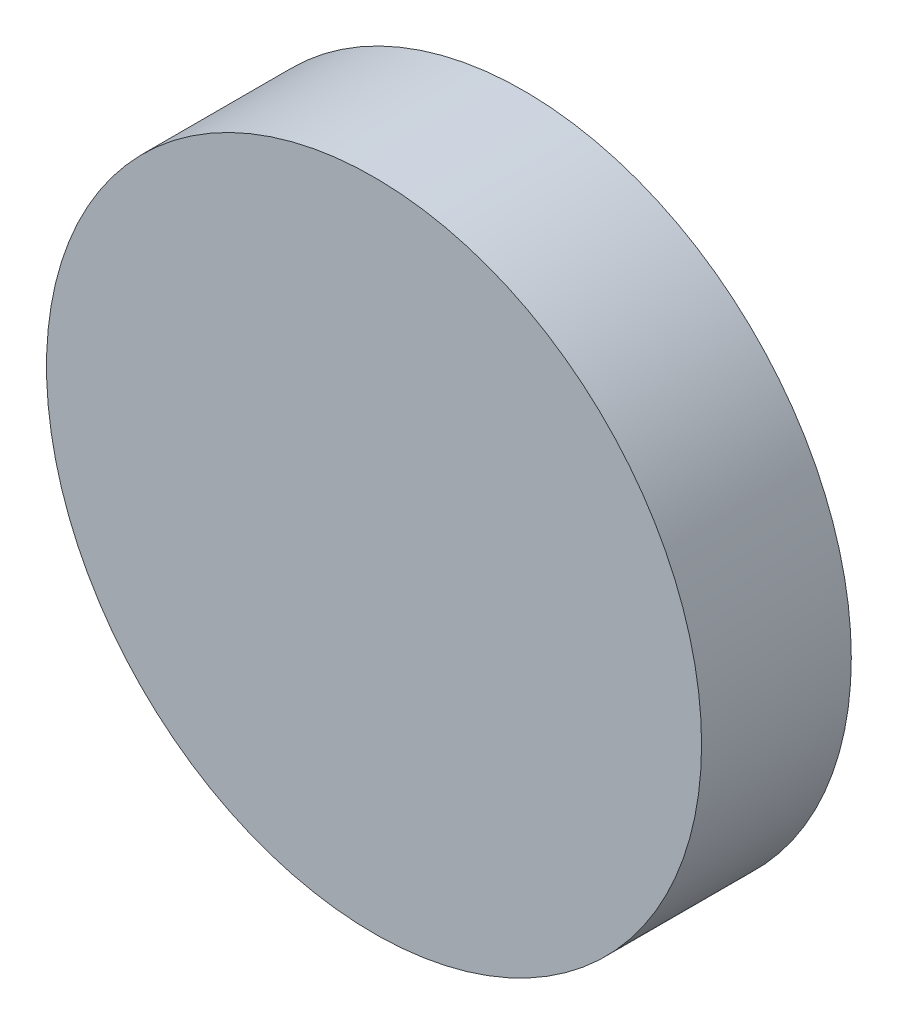
SolidWorks part; units mm, degrees
ref_plane "Front Plane" through (0, 0, 0) normal (0, 0, 1) x (1, 0, 0)
ref_plane "Top Plane" through (0, 0, 0) normal (0, 1, 0) x (1, 0, 0)
ref_plane "Right Plane" through (0, 0, 0) normal (1, 0, 0) x (0, 0, -1)
sketch "Sketch3" plane through (0, 0, 0) normal (0, 0, 1) x (1, 0, 0)
  circle A0 centre (0, 0) radius 175
  point P0 (0, 0)
  dimension "D1" = 350
extrude "Boss-Extrude1" add sketch "Sketch3" along normal blind 80 contours A0
